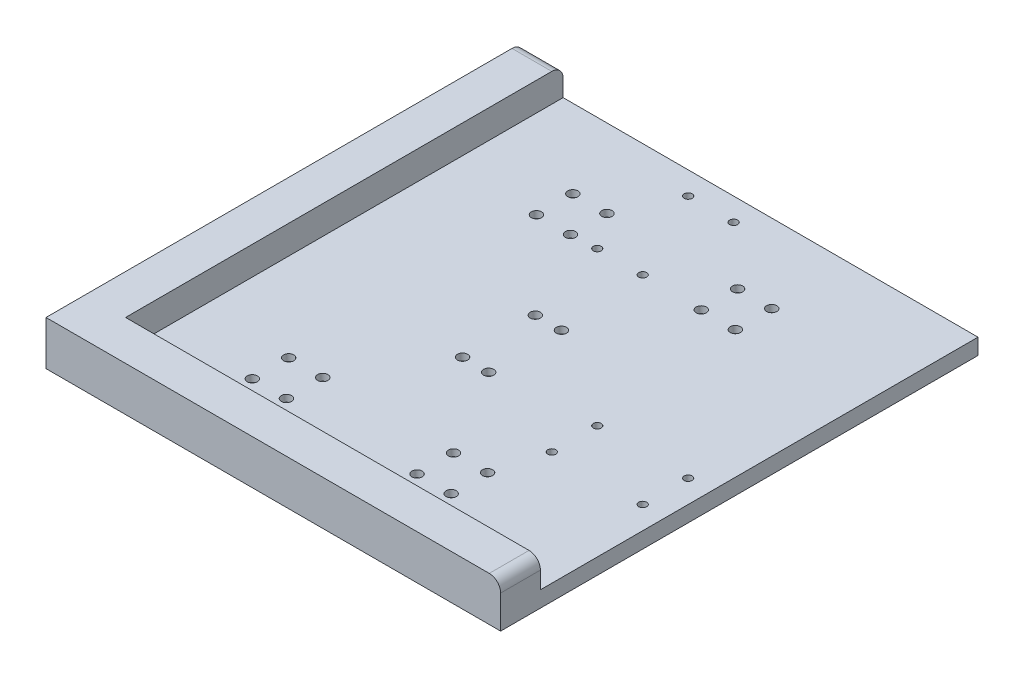
SolidWorks part; units mm, degrees
material "1.0037 (S235JR)"
ref_plane "Płaszczyzna przednia" through (0, 0, 0) normal (0, 0, 1) x (1, 0, 0)
ref_plane "Płaszczyzna górna" through (0, 0, 0) normal (0, 1, 0) x (1, 0, 0)
ref_plane "Płaszczyzna prawa" through (0, 0, 0) normal (1, 0, 0) x (0, 0, -1)
sketch "Szkic1" plane through (0, 0, 0) normal (0, 1, 0) x (1, 0, 0)
  line L1 (-200, -210) -> (200, -210)
  line L2 (-200, -210) -> (-200, 210)
  line L3 (-200, 210) -> (200, 210)
  line L4 (200, -210) -> (200, 210)
  line L5 (-200, -210) -> (200, 210) construction
  line L6 (-200, 210) -> (200, -210) construction
  point P0 (0, 0)
  dimension "D1" = 420
  dimension "D2" = 400
extrude "Dodanie-wyciągnięcie1" add sketch "Szkic1" along normal blind 14
sketch "Szkic2" plane through (0, 0, 0) normal (0, -1, 0) x (1, 0, 0)
  line L2 (-95, -147.5) -> (95, -147.5)
  line L3 (-95, -147.5) -> (-95, 147.5)
  line L4 (-95, 147.5) -> (95, 147.5)
  line L5 (95, -147.5) -> (95, 147.5)
  line L6 (-95, -147.5) -> (95, 147.5) construction
  line L7 (-95, 147.5) -> (95, -147.5) construction
  point P4 (0, 0)
  dimension "D1" = 190
  dimension "D2" = 295
hole_wizard "Pogłębienie walcowe pod M5 Wkręt do części metalowych z łbem sześciokątnym1" positions "Szkic7" profile "Szkic6" counterbore size "M5" standard "Ansi Metric" end condition through all
sketch "Szkic7" plane through (0, 14, 0) normal (0, 1, 0) x (1, 0, 0)
  point P0 (-87.5, -141)
  point P2 (-87.5, -109)
  point P4 (-57.5, -141)
  point P6 (-57.5, -109)
  point P8 (57.5, -141)
  point P10 (57.5, -109)
  point P12 (87.5, -109)
  point P14 (87.5, -141)
sketch "Szkic6" plane through (-87.5, 14, 141) normal (1, 0, 0) x (0, 0, 1)
  line L0 (0, 0) -> (0, 14)
  line L1 (0, 14) -> (2.75, 14)
  line L3 (2.75, 14) -> (2.75, 6)
  line L4 (2.75, 6) -> (4.5, 6)
  line L5 (4.5, 6) -> (4.5, 0)
  line L7 (4.5, 0) -> (0, 0)
  line L11 (0, -6.35) -> (0, 107.95) construction
  dimension "Średnica otworu na wylot" = 5.5
  dimension "Głębokość otworu na wylot" = 14
  dimension "Średnica pogłębienia walcowego" = 9
  dimension "Głębokość pogłębienia walcowego" = 6
mirror "Lustro3" about plane through (0, 0, 0) normal (0, 0, 1) of "Pogłębienie walcowe pod M5 Wkręt do części metalowych z łbem sześciokątnym1"
sketch "Szkic10" plane through (-200, 0, 0) normal (-1, 0, 0) x (0, 0, 1)
  line L1 (-35, 0) -> (35, 0)
  line L2 (-35, 0) -> (-35, 4)
  line L3 (-35, 4) -> (35, 4)
  line L4 (35, 0) -> (35, 4)
  dimension "D1" = 70
  dimension "D2" = 4
extrude "Wytnij-wyciągnięcie1" cut sketch "Szkic10" against normal blind 50
fillet "Zaokrąglenie1" radius 10 2 edges at (-150, 2, -35) (-150, 2, 35)
sketch "草图1" plane through (0, 14, 0) normal (0, 1, 0) x (1, 0, 0)
  line L0 (200, 0) -> (-245.0175, 0) construction
  line L1 (200, -210) -> (200, 210) construction
  line L2 (0, 210) -> (0, -345.7386) construction
  line L3 (200, 210) -> (-200, 210) construction
  circle A0 centre (11.5, 32) radius 4.5
  circle A1 centre (-11.5, 32) radius 4.5
  circle A2 centre (-11.5, -32) radius 4.5
  circle A3 centre (11.5, -32) radius 4.5
  dimension "D1" = 64
  dimension "D2" = 23
extrude "切除-拉伸1" cut sketch "草图1" against normal blind 6
sketch "草图2" plane through (0, 14, 0) normal (0, 1, 0) x (1, 0, 0)
  line L0 (200, 0) -> (-231.194, 0) construction
  line L1 (200, -210) -> (200, 210) construction
  line L2 (0, 210) -> (0, -258.8119) construction
  line L3 (200, 210) -> (-200, 210) construction
  circle A0 centre (11.5, 32) radius 2.75
  circle A1 centre (-11.5, 32) radius 2.75
  circle A2 centre (-11.5, -32) radius 2.75
  circle A3 centre (11.5, -32) radius 2.75
  dimension "D1" = 5.5
extrude "切除-拉伸2" cut sketch "草图2" against normal through all
sketch "草图4" plane through (0, 14, 0) normal (0, 1, 0) x (1, 0, 0)
  line L0 (-200, 210) -> (-200, -210)
  line L1 (-200, -210) -> (200, -210)
  line L2 (200, -210) -> (200, -175)
  line L3 (200, -210) -> (200, 210) construction
  line L4 (200, -175) -> (-165, -175)
  line L5 (-165, -175) -> (-165, 210)
  line L6 (200, 210) -> (-200, 210) construction
  line L7 (-165, 210) -> (-200, 210)
  dimension "D1" = 35
  dimension "D2" = 35
extrude "凸台-拉伸2" add sketch "草图4" along normal blind 25
fillet "圆角3" radius 10 1 edges at (200, 39, 192.5)
fillet "圆角4" radius 10 1 edges at (-182.5, 39, -210)
sketch "草图5" plane through (0, 14, 0) normal (0, 1, 0) x (1, 0, 0)
  line L0 (200, -175) -> (200, 210) construction
  line L1 (55.3096, -45) -> (232.96, -45) construction
  line L2 (190, -175) -> (-165, -175) construction
  line L3 (-15, 64.5763) -> (-15, 278.7927) construction
  line L4 (200, 210) -> (-165, 210) construction
  line L5 (-165, -175) -> (-165, 200) construction
  circle A0 centre (100, -65) radius 3.5
  circle A3 centre (180, -65) radius 3.5
  circle A4 centre (180, -25) radius 3.5
  circle A5 centre (100, -25) radius 3.5
  circle A6 centre (5, 110) radius 3.5
  circle A7 centre (5, 190) radius 3.5
  circle A8 centre (-35, 190) radius 3.5
  circle A9 centre (-35, 110) radius 3.5
  point P28 (0, 0)
  dimension "D1" = 7
  dimension "D2" = 20
  dimension "D3" = 7
  dimension "D4" = 130
  dimension "D8" = 7
  dimension "D9" = 7
  dimension "D10" = 20
  dimension "D11" = 20
  dimension "D12" = 80
  dimension "D13" = 20
  dimension "D5" = 80
  dimension "D6" = 20
  dimension "D7" = 20
  dimension "D14" = 150
extrude "切除-拉伸3" cut sketch "草图5" against normal through all contours A0 | A5 | A3 | A4 | A6 | A9 | A8 | A7
